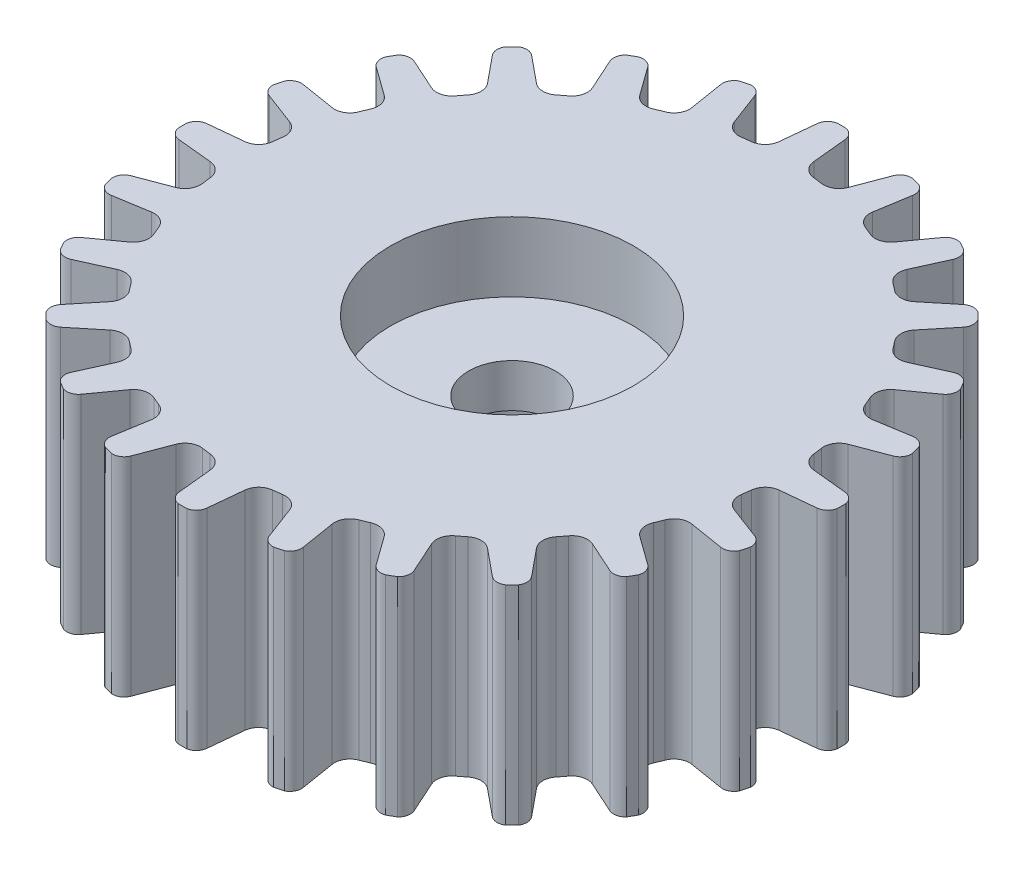
SolidWorks part; units mm, degrees
ref_plane "Front Plane" through (0, 0, 0) normal (0, 0, 1) x (1, 0, 0)
ref_plane "Top Plane" through (0, 0, 0) normal (0, 1, 0) x (1, 0, 0)
ref_plane "Right Plane" through (0, 0, 0) normal (1, 0, 0) x (0, 0, -1)
sketch "Sketch1" plane through (0, 0, 0) normal (0, 1, 0) x (1, 0, 0)
  circle A0 centre (0, 0) radius 2.25
  circle A1 centre (0, 0) radius 9.5
  dimension "D1" = 4.5
  dimension "D2" = 19
extrude "Boss-Extrude1" add sketch "Sketch1" along normal blind 6
sketch "Sketch2" plane through (0, 6, 0) normal (0, 1, 0) x (1, 0, 0)
  line L0 (0, 0) -> (0, 10.7871) construction
  line L1 (0.5, 8.2) -> (0.4, 9.2)
  line L2 (-0.5, 8.2) -> (-0.4, 9.2)
  line L3 (2.6053, 7.7912) -> (2.7675, 8.783)
  line L4 (1.6394, 8.05) -> (1.9948, 8.99)
  line L5 (4.533, 6.8514) -> (4.9464, 7.7674)
  line L6 (3.667, 7.3514) -> (4.2536, 8.1674)
  line L7 (6.1518, 5.4447) -> (6.7882, 6.2225)
  line L8 (5.4447, 6.1518) -> (6.2225, 6.7882)
  line L9 (7.3514, 3.667) -> (8.1674, 4.2536)
  line L10 (6.8514, 4.533) -> (7.7674, 4.9464)
  line L11 (8.05, 1.6394) -> (8.99, 1.9948)
  line L12 (7.7912, 2.6053) -> (8.783, 2.7675)
  line L13 (8.2, -0.5) -> (9.2, -0.4)
  line L14 (8.2, 0.5) -> (9.2, 0.4)
  line L15 (7.7912, -2.6053) -> (8.783, -2.7675)
  line L16 (8.05, -1.6394) -> (8.99, -1.9948)
  line L17 (6.8514, -4.533) -> (7.7674, -4.9464)
  line L18 (7.3514, -3.667) -> (8.1674, -4.2536)
  line L19 (5.4447, -6.1518) -> (6.2225, -6.7882)
  line L20 (6.1518, -5.4447) -> (6.7882, -6.2225)
  line L21 (3.667, -7.3514) -> (4.2536, -8.1674)
  line L22 (4.533, -6.8514) -> (4.9464, -7.7674)
  line L23 (1.6394, -8.05) -> (1.9948, -8.99)
  line L24 (2.6053, -7.7912) -> (2.7675, -8.783)
  line L25 (-0.5, -8.2) -> (-0.4, -9.2)
  line L26 (0.5, -8.2) -> (0.4, -9.2)
  line L27 (-2.6053, -7.7912) -> (-2.7675, -8.783)
  line L28 (-1.6394, -8.05) -> (-1.9948, -8.99)
  line L29 (-4.533, -6.8514) -> (-4.9464, -7.7674)
  line L30 (-3.667, -7.3514) -> (-4.2536, -8.1674)
  line L31 (-6.1518, -5.4447) -> (-6.7882, -6.2225)
  line L32 (-5.4447, -6.1518) -> (-6.2225, -6.7882)
  line L33 (-7.3514, -3.667) -> (-8.1674, -4.2536)
  line L34 (-6.8514, -4.533) -> (-7.7674, -4.9464)
  line L35 (-8.05, -1.6394) -> (-8.99, -1.9948)
  line L36 (-7.7912, -2.6053) -> (-8.783, -2.7675)
  line L37 (-8.2, 0.5) -> (-9.2, 0.4)
  line L38 (-8.2, -0.5) -> (-9.2, -0.4)
  line L39 (-7.7912, 2.6053) -> (-8.783, 2.7675)
  line L40 (-8.05, 1.6394) -> (-8.99, 1.9948)
  line L41 (-6.8514, 4.533) -> (-7.7674, 4.9464)
  line L42 (-7.3514, 3.667) -> (-8.1674, 4.2536)
  line L43 (-5.4447, 6.1518) -> (-6.2225, 6.7882)
  line L44 (-6.1518, 5.4447) -> (-6.7882, 6.2225)
  line L45 (-3.667, 7.3514) -> (-4.2536, 8.1674)
  line L46 (-4.533, 6.8514) -> (-4.9464, 7.7674)
  line L47 (-1.6394, 8.05) -> (-1.9948, 8.99)
  line L48 (-2.6053, 7.7912) -> (-2.7675, 8.783)
  arc A0 (2.8881, 7.3013) -> (3.1206, 7.205) centre (0, 0) cw
  arc A2 (0.9, 7.8) -> (1.1495, 7.7672) centre (0, 0) cw
  arc A3 (0.5, 8.2) -> (0.9, 7.8) centre (0.9444, 8.2444) ccw
  arc A4 (0, 9.5) -> (0.4, 9.2) centre (0.0622, 9.1662) cw
  arc A5 (-0.5, 8.2) -> (-0.9, 7.8) centre (-0.9444, 8.2444) cw
  arc A6 (0, 9.5) -> (-0.4, 9.2) centre (-0.0622, 9.1662) ccw
  arc A7 (2.6053, 7.7912) -> (2.8881, 7.3013) centre (3.0461, 7.7191) ccw
  arc A8 (2.4588, 9.1763) -> (2.7675, 8.783) centre (2.4324, 8.8378) cw
  arc A9 (1.6394, 8.05) -> (1.1495, 7.7672) centre (1.2216, 8.208) cw
  arc A10 (2.4588, 9.1763) -> (1.9948, 8.99) centre (2.3123, 8.87) ccw
  arc A11 (4.6794, 6.305) -> (4.879, 6.1518) centre (0, 0) cw
  arc A12 (4.533, 6.8514) -> (4.6794, 6.305) centre (4.9401, 6.6677) ccw
  arc A13 (4.75, 8.2272) -> (4.9464, 7.7674) centre (4.6369, 7.9071) cw
  arc A14 (3.667, 7.3514) -> (3.1206, 7.205) centre (3.3043, 7.6121) cw
  arc A15 (4.75, 8.2272) -> (4.2536, 8.1674) centre (4.5293, 7.9693) ccw
  arc A16 (6.1518, 4.879) -> (6.305, 4.6794) centre (0, 0) cw
  arc A17 (6.1518, 5.4447) -> (6.1518, 4.879) centre (6.4975, 5.1619) ccw
  arc A18 (6.7175, 6.7175) -> (6.7882, 6.2225) centre (6.5254, 6.4375) cw
  arc A19 (5.4447, 6.1518) -> (4.879, 6.1518) centre (5.1619, 6.4975) cw
  arc A20 (6.7175, 6.7175) -> (6.2225, 6.7882) centre (6.4375, 6.5254) ccw
  arc A21 (7.205, 3.1206) -> (7.3013, 2.8881) centre (0, 0) cw
  arc A22 (7.3514, 3.667) -> (7.205, 3.1206) centre (7.6121, 3.3043) ccw
  arc A23 (8.2272, 4.75) -> (8.1674, 4.2536) centre (7.9693, 4.5293) cw
  arc A24 (6.8514, 4.533) -> (6.305, 4.6794) centre (6.6677, 4.9401) cw
  arc A25 (8.2272, 4.75) -> (7.7674, 4.9464) centre (7.9071, 4.6369) ccw
  arc A26 (7.7672, 1.1495) -> (7.8, 0.9) centre (0, 0) cw
  arc A27 (8.05, 1.6394) -> (7.7672, 1.1495) centre (8.208, 1.2216) ccw
  arc A28 (9.1763, 2.4588) -> (8.99, 1.9948) centre (8.87, 2.3123) cw
  arc A29 (7.7912, 2.6053) -> (7.3013, 2.8881) centre (7.7191, 3.0461) cw
  arc A30 (9.1763, 2.4588) -> (8.783, 2.7675) centre (8.8378, 2.4324) ccw
  arc A31 (7.8, -0.9) -> (7.7672, -1.1495) centre (0, 0) cw
  arc A32 (8.2, -0.5) -> (7.8, -0.9) centre (8.2444, -0.9444) ccw
  arc A33 (9.5, 0) -> (9.2, -0.4) centre (9.1662, -0.0622) cw
  arc A34 (8.2, 0.5) -> (7.8, 0.9) centre (8.2444, 0.9444) cw
  arc A35 (9.5, 0) -> (9.2, 0.4) centre (9.1662, 0.0622) ccw
  arc A36 (7.3013, -2.8881) -> (7.205, -3.1206) centre (0, 0) cw
  arc A37 (7.7912, -2.6053) -> (7.3013, -2.8881) centre (7.7191, -3.0461) ccw
  arc A38 (9.1763, -2.4588) -> (8.783, -2.7675) centre (8.8378, -2.4324) cw
  arc A39 (8.05, -1.6394) -> (7.7672, -1.1495) centre (8.208, -1.2216) cw
  arc A40 (9.1763, -2.4588) -> (8.99, -1.9948) centre (8.87, -2.3123) ccw
  arc A41 (6.305, -4.6794) -> (6.1518, -4.879) centre (0, 0) cw
  arc A42 (6.8514, -4.533) -> (6.305, -4.6794) centre (6.6677, -4.9401) ccw
  arc A43 (8.2272, -4.75) -> (7.7674, -4.9464) centre (7.9071, -4.6369) cw
  arc A44 (7.3514, -3.667) -> (7.205, -3.1206) centre (7.6121, -3.3043) cw
  arc A45 (8.2272, -4.75) -> (8.1674, -4.2536) centre (7.9693, -4.5293) ccw
  arc A46 (4.879, -6.1518) -> (4.6794, -6.305) centre (0, 0) cw
  arc A47 (5.4447, -6.1518) -> (4.879, -6.1518) centre (5.1619, -6.4975) ccw
  arc A48 (6.7175, -6.7175) -> (6.2225, -6.7882) centre (6.4375, -6.5254) cw
  arc A49 (6.1518, -5.4447) -> (6.1518, -4.879) centre (6.4975, -5.1619) cw
  arc A50 (6.7175, -6.7175) -> (6.7882, -6.2225) centre (6.5254, -6.4375) ccw
  arc A51 (3.1206, -7.205) -> (2.8881, -7.3013) centre (0, 0) cw
  arc A52 (3.667, -7.3514) -> (3.1206, -7.205) centre (3.3043, -7.6121) ccw
  arc A53 (4.75, -8.2272) -> (4.2536, -8.1674) centre (4.5293, -7.9693) cw
  arc A54 (4.533, -6.8514) -> (4.6794, -6.305) centre (4.9401, -6.6677) cw
  arc A55 (4.75, -8.2272) -> (4.9464, -7.7674) centre (4.6369, -7.9071) ccw
  arc A56 (1.1495, -7.7672) -> (0.9, -7.8) centre (0, 0) cw
  arc A57 (1.6394, -8.05) -> (1.1495, -7.7672) centre (1.2216, -8.208) ccw
  arc A58 (2.4588, -9.1763) -> (1.9948, -8.99) centre (2.3123, -8.87) cw
  arc A59 (2.6053, -7.7912) -> (2.8881, -7.3013) centre (3.0461, -7.7191) cw
  arc A60 (2.4588, -9.1763) -> (2.7675, -8.783) centre (2.4324, -8.8378) ccw
  arc A61 (-0.9, -7.8) -> (-1.1495, -7.7672) centre (0, 0) cw
  arc A62 (-0.5, -8.2) -> (-0.9, -7.8) centre (-0.9444, -8.2444) ccw
  arc A63 (0, -9.5) -> (-0.4, -9.2) centre (-0.0622, -9.1662) cw
  arc A64 (0.5, -8.2) -> (0.9, -7.8) centre (0.9444, -8.2444) cw
  arc A65 (0, -9.5) -> (0.4, -9.2) centre (0.0622, -9.1662) ccw
  arc A66 (-2.8881, -7.3013) -> (-3.1206, -7.205) centre (0, 0) cw
  arc A67 (-2.6053, -7.7912) -> (-2.8881, -7.3013) centre (-3.0461, -7.7191) ccw
  arc A68 (-2.4588, -9.1763) -> (-2.7675, -8.783) centre (-2.4324, -8.8378) cw
  arc A69 (-1.6394, -8.05) -> (-1.1495, -7.7672) centre (-1.2216, -8.208) cw
  arc A70 (-2.4588, -9.1763) -> (-1.9948, -8.99) centre (-2.3123, -8.87) ccw
  arc A71 (-4.6794, -6.305) -> (-4.879, -6.1518) centre (0, 0) cw
  arc A72 (-4.533, -6.8514) -> (-4.6794, -6.305) centre (-4.9401, -6.6677) ccw
  arc A73 (-4.75, -8.2272) -> (-4.9464, -7.7674) centre (-4.6369, -7.9071) cw
  arc A74 (-3.667, -7.3514) -> (-3.1206, -7.205) centre (-3.3043, -7.6121) cw
  arc A75 (-4.75, -8.2272) -> (-4.2536, -8.1674) centre (-4.5293, -7.9693) ccw
  arc A76 (-6.1518, -4.879) -> (-6.305, -4.6794) centre (0, 0) cw
  arc A77 (-6.1518, -5.4447) -> (-6.1518, -4.879) centre (-6.4975, -5.1619) ccw
  arc A78 (-6.7175, -6.7175) -> (-6.7882, -6.2225) centre (-6.5254, -6.4375) cw
  arc A79 (-5.4447, -6.1518) -> (-4.879, -6.1518) centre (-5.1619, -6.4975) cw
  arc A80 (-6.7175, -6.7175) -> (-6.2225, -6.7882) centre (-6.4375, -6.5254) ccw
  arc A81 (-7.205, -3.1206) -> (-7.3013, -2.8881) centre (0, 0) cw
  arc A82 (-7.3514, -3.667) -> (-7.205, -3.1206) centre (-7.6121, -3.3043) ccw
  arc A83 (-8.2272, -4.75) -> (-8.1674, -4.2536) centre (-7.9693, -4.5293) cw
  arc A84 (-6.8514, -4.533) -> (-6.305, -4.6794) centre (-6.6677, -4.9401) cw
  arc A85 (-8.2272, -4.75) -> (-7.7674, -4.9464) centre (-7.9071, -4.6369) ccw
  arc A86 (-7.7672, -1.1495) -> (-7.8, -0.9) centre (0, 0) cw
  arc A87 (-8.05, -1.6394) -> (-7.7672, -1.1495) centre (-8.208, -1.2216) ccw
  arc A88 (-9.1763, -2.4588) -> (-8.99, -1.9948) centre (-8.87, -2.3123) cw
  arc A89 (-7.7912, -2.6053) -> (-7.3013, -2.8881) centre (-7.7191, -3.0461) cw
  arc A90 (-9.1763, -2.4588) -> (-8.783, -2.7675) centre (-8.8378, -2.4324) ccw
  arc A91 (-7.8, 0.9) -> (-7.7672, 1.1495) centre (0, 0) cw
  arc A92 (-8.2, 0.5) -> (-7.8, 0.9) centre (-8.2444, 0.9444) ccw
  arc A93 (-9.5, 0) -> (-9.2, 0.4) centre (-9.1662, 0.0622) cw
  arc A94 (-8.2, -0.5) -> (-7.8, -0.9) centre (-8.2444, -0.9444) cw
  arc A95 (-9.5, 0) -> (-9.2, -0.4) centre (-9.1662, -0.0622) ccw
  arc A96 (-7.3013, 2.8881) -> (-7.205, 3.1206) centre (0, 0) cw
  arc A97 (-7.7912, 2.6053) -> (-7.3013, 2.8881) centre (-7.7191, 3.0461) ccw
  arc A98 (-9.1763, 2.4588) -> (-8.783, 2.7675) centre (-8.8378, 2.4324) cw
  arc A99 (-8.05, 1.6394) -> (-7.7672, 1.1495) centre (-8.208, 1.2216) cw
  arc A100 (-9.1763, 2.4588) -> (-8.99, 1.9948) centre (-8.87, 2.3123) ccw
  arc A101 (-6.305, 4.6794) -> (-6.1518, 4.879) centre (0, 0) cw
  arc A102 (-6.8514, 4.533) -> (-6.305, 4.6794) centre (-6.6677, 4.9401) ccw
  arc A103 (-8.2272, 4.75) -> (-7.7674, 4.9464) centre (-7.9071, 4.6369) cw
  arc A104 (-7.3514, 3.667) -> (-7.205, 3.1206) centre (-7.6121, 3.3043) cw
  arc A105 (-8.2272, 4.75) -> (-8.1674, 4.2536) centre (-7.9693, 4.5293) ccw
  arc A106 (-4.879, 6.1518) -> (-4.6794, 6.305) centre (0, 0) cw
  arc A107 (-5.4447, 6.1518) -> (-4.879, 6.1518) centre (-5.1619, 6.4975) ccw
  arc A108 (-6.7175, 6.7175) -> (-6.2225, 6.7882) centre (-6.4375, 6.5254) cw
  arc A109 (-6.1518, 5.4447) -> (-6.1518, 4.879) centre (-6.4975, 5.1619) cw
  arc A110 (-6.7175, 6.7175) -> (-6.7882, 6.2225) centre (-6.5254, 6.4375) ccw
  arc A111 (-3.1206, 7.205) -> (-2.8881, 7.3013) centre (0, 0) cw
  arc A112 (-3.667, 7.3514) -> (-3.1206, 7.205) centre (-3.3043, 7.6121) ccw
  arc A113 (-4.75, 8.2272) -> (-4.2536, 8.1674) centre (-4.5293, 7.9693) cw
  arc A114 (-4.533, 6.8514) -> (-4.6794, 6.305) centre (-4.9401, 6.6677) cw
  arc A115 (-4.75, 8.2272) -> (-4.9464, 7.7674) centre (-4.6369, 7.9071) ccw
  arc A116 (-1.1495, 7.7672) -> (-0.9, 7.8) centre (0, 0) cw
  arc A117 (-1.6394, 8.05) -> (-1.1495, 7.7672) centre (-1.2216, 8.208) ccw
  arc A118 (-2.4588, 9.1763) -> (-1.9948, 8.99) centre (-2.3123, 8.87) cw
  arc A119 (-2.6053, 7.7912) -> (-2.8881, 7.3013) centre (-3.0461, 7.7191) cw
  arc A120 (-2.4588, 9.1763) -> (-2.7675, 8.783) centre (-2.4324, 8.8378) ccw
  circle A121 centre (0, 0) radius 9.5 construction
  circle A132 centre (0, 0) radius 11.1781
  point P296 (0, 0)
  dimension "D7" = 24
  dimension "D1" = 0.4
  dimension "D2" = 0.1
  dimension "D3" = 1
  dimension "D4" = 0.3
  dimension "D5" = 0.4
  dimension "D6" = 0.4
extrude "Cut-Extrude1" cut sketch "Sketch2" against normal up to next
sketch "Sketch3" plane through (0, 6, 0) normal (0, 1, 0) x (1, 0, 0)
  circle A0 centre (0, 0) radius 2.25 construction
  circle A1 centre (0, 0) radius 2.25
  circle A2 centre (0, 0) radius 1.25
  dimension "D1" = 2.5
extrude "Boss-Extrude2" add sketch "Sketch3" against normal blind 3.25
sketch "Sketch4" plane through (0, 6, 0) normal (0, 1, 0) x (1, 0, 0)
  circle A0 centre (0, 0) radius 3.5
  dimension "D1" = 7
extrude "Cut-Extrude2" cut sketch "Sketch4" against normal blind 2
